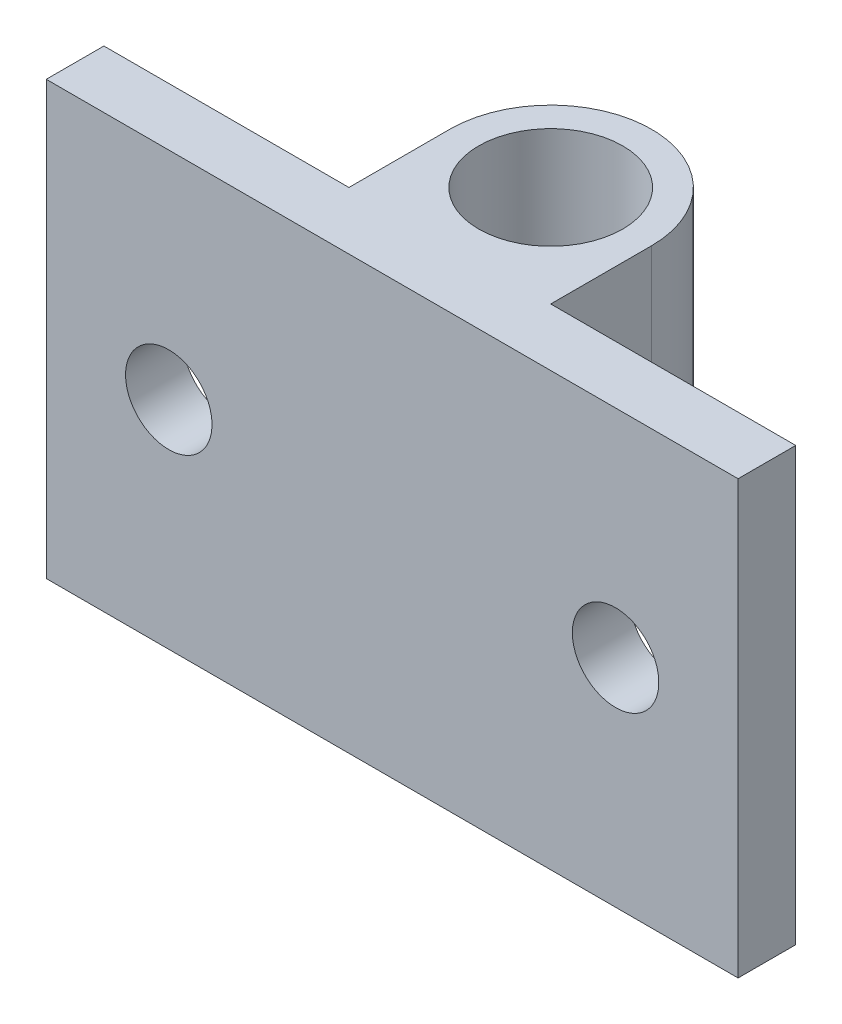
SolidWorks part; units mm, degrees
ref_plane "Front" through (0, 0, 0) normal (0, 0, 1) x (1, 0, 0)
ref_plane "Top" through (0, 0, 0) normal (0, 1, 0) x (1, 0, 0)
ref_plane "Right" through (0, 0, 0) normal (1, 0, 0) x (0, 0, -1)
sketch "Sketch1" plane through (0, 0, 0) normal (0, 1, 0) x (1, 0, 0)
  line L0 (0, 0) -> (0, -5.5)
  line L1 (0, -5.5) -> (12, -5.5)
  line L2 (0, -5.5) -> (-12, -5.5)
  line L3 (-12, -5.5) -> (-12, -3.5)
  line L4 (0, 2.5) -> (0, 3.5)
  line L5 (-2.5, 0) -> (-3.5, 0)
  line L6 (2.5, 0) -> (3.5, 0)
  line L7 (-3.5, 0) -> (-3.5, -3.5)
  line L8 (-3.5, -3.5) -> (-12, -3.5)
  line L9 (3.5, 0) -> (3.5, -3.5)
  line L10 (12, -5.5) -> (12, -3.5)
  line L11 (12, -3.5) -> (3.5, -3.5)
  circle A0 centre (0, 0) radius 2.5
  arc A1 (-3.5, 0) -> (3.5, 0) centre (0, 0) cw
  dimension "D1" = 12
  dimension "D3" = 5.5
  dimension "D4" = 2
  dimension "D2" = 12
  dimension "D5" = 1
  dimension "D6" = 1
  dimension "D7" = 1
extrude "Boss-Extrude1" add sketch "Sketch1" along normal blind 15 contours A1 L4 A0 L6 | A1 L5 A0 L4 | A0 L5 L7 L8 L3 L2 L0 | A0 L0 L1 L10 L11 L9 L6
sketch "Sketch2" plane through (0, 0, 3.5) normal (0, 0, -1) x (-1, 0, 0)
  line L0 (7.75, 15) -> (7.75, 0)
  line L1 (3.5, 15) -> (12, 15) construction
  line L2 (3.5, 0) -> (12, 0) construction
  line L3 (-7.75, 15) -> (-7.75, 0)
  line L4 (-12, 15) -> (-3.5, 15) construction
  line L5 (-12, 0) -> (-3.5, 0) construction
  circle A0 centre (7.75, 7.5) radius 1.5
  circle A1 centre (-7.75, 7.5) radius 1.5
extrude "Cut-Extrude1" cut sketch "Sketch2" against normal through all contours L3 A1 | L3 A1 | L0 A0 | L0 A0
sketch "Sketch3" plane through (0, 0, 3.5) normal (0, 0, -1) x (-1, 0, 0)
  line L0 (3.5, 0) -> (3.5, 7.5)
  line L1 (3.5, 15) -> (3.5, 0) construction
  line L2 (3.5, 7.5) -> (-3.5, 7.5)
  line L3 (-3.5, 15) -> (-3.5, 0) construction
  line L4 (-3.5, 7.5) -> (-3.5, 0)
  line L5 (-3.5, 0) -> (3.5, 0)
extrude "Cut-Extrude2" cut sketch "Sketch3" along normal through all
